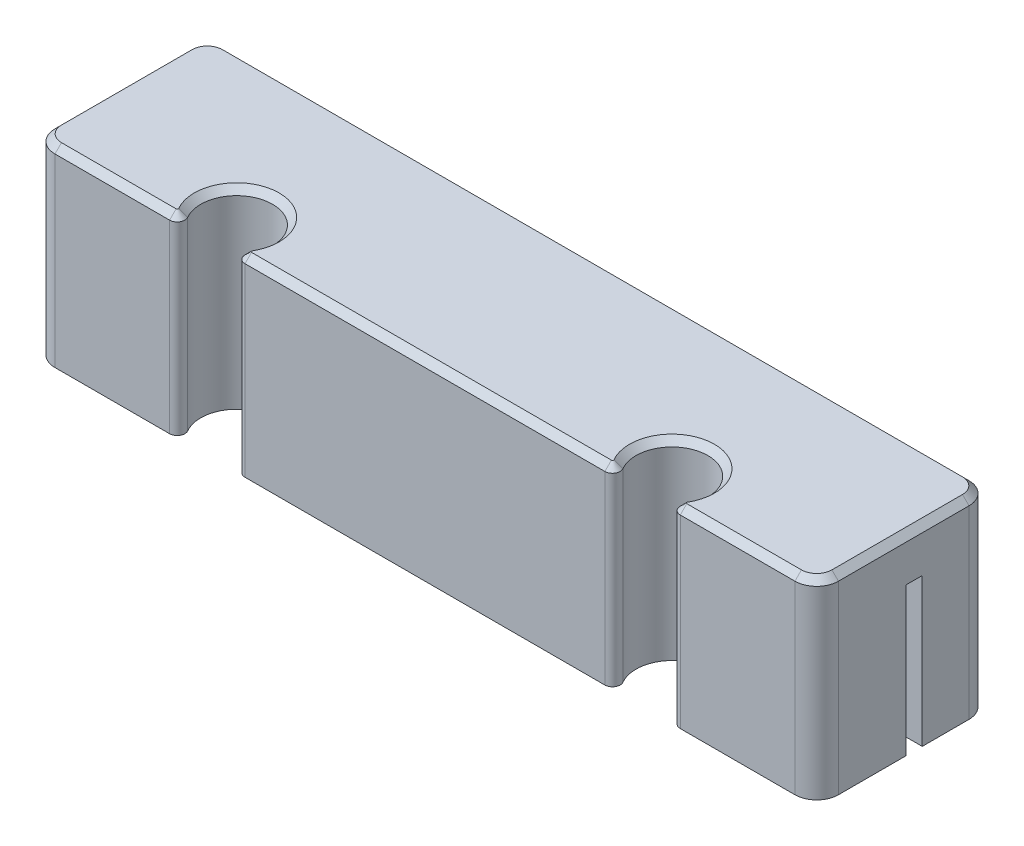
SolidWorks part; units mm, degrees
ref_plane "Front Plane" through (0, 0, 0) normal (0, 0, 1) x (1, 0, 0)
ref_plane "Top Plane" through (0, 0, 0) normal (0, 1, 0) x (1, 0, 0)
ref_plane "Right Plane" through (0, 0, 0) normal (1, 0, 0) x (0, 0, -1)
sketch "Sketch1" plane through (0, 0, 0) normal (0, 1, 0) x (1, 0, 0)
  line L0 (0, 19.8821) -> (0, -11.3954) construction
  line L1 (0, 0) -> (-18, 0)
  line L2 (0, -3.15) -> (-0.8, -3.15)
  line L3 (-0.8, -3.15) -> (-0.8, -2)
  line L4 (-0.8, -2) -> (-2, -2)
  line L5 (-2, -2) -> (-2, -3.15)
  line L6 (-2, -3.15) -> (-2.8, -3.15)
  line L7 (-2.8, -3.15) -> (-2.8, -2)
  line L8 (-2.8, -2) -> (-4, -2)
  line L9 (-4, -2) -> (-4, -3.15)
  line L10 (-4, -3.15) -> (-4.8, -3.15)
  line L11 (-4.8, -3.15) -> (-4.8, -2)
  line L12 (-4.8, -2) -> (-6, -2)
  line L13 (-6, -2) -> (-6, -3.15)
  line L14 (-6, -3.15) -> (-6.8, -3.15)
  line L15 (-6.8, -3.15) -> (-6.8, -2)
  line L16 (-6.8, -2) -> (-8, -2)
  line L17 (-8, -2) -> (-8, -3.15)
  line L18 (-8, -3.15) -> (-8.8, -3.15)
  line L19 (-8.8, -3.15) -> (-8.8, -2)
  line L20 (-8.8, -2) -> (-10, -2)
  line L21 (-10, -2) -> (-10, -3.15)
  line L22 (-10, -3.15) -> (-10.8, -3.15)
  line L23 (-10.8, -3.15) -> (-10.8, -2)
  line L24 (-10.8, -2) -> (-12, -2)
  line L25 (-12, -2) -> (-12, -3.15)
  line L26 (-12, -3.15) -> (-12.8, -3.15)
  line L27 (-12.8, -3.15) -> (-12.8, -2)
  line L28 (-12.8, -2) -> (-14, -2)
  line L29 (-14, -2) -> (-14, -3.15)
  line L30 (-14, -3.15) -> (-14.8, -3.15)
  line L31 (-14.8, -3.15) -> (-14.8, -2)
  line L32 (-14.8, -2) -> (-16, -2)
  line L33 (-16, -2) -> (-16, -3.15)
  line L34 (-16, -3.15) -> (-16.8, -3.15)
  line L35 (-16.8, -3.15) -> (-16.8, -2)
  line L36 (-16.8, -2) -> (-18, -2)
  line L38 (-18, -2) -> (-18, -3.15) [skipped]
  line L40 (0, -3.15) -> (0, -2)
  line L41 (0, -2) -> (1.2, -2)
  line L42 (1.2, -2) -> (1.2, -3.15)
  line L43 (1.2, -3.15) -> (2, -3.15)
  line L44 (2, -3.15) -> (2, -2)
  line L45 (2, -2) -> (3.2, -2)
  line L46 (3.2, -2) -> (3.2, -3.15)
  line L47 (3.2, -3.15) -> (4, -3.15)
  line L48 (4, -3.15) -> (4, -2)
  line L49 (4, -2) -> (5.2, -2)
  line L50 (5.2, -2) -> (5.2, -3.15)
  line L51 (5.2, -3.15) -> (6, -3.15)
  line L52 (6, -3.15) -> (6, -2)
  line L53 (6, -2) -> (7.2, -2)
  line L54 (7.2, -2) -> (7.2, -3.15)
  line L55 (7.2, -3.15) -> (8, -3.15)
  line L56 (8, -3.15) -> (8, -2)
  line L57 (8, -2) -> (9.2, -2)
  line L58 (9.2, -2) -> (9.2, -3.15)
  line L59 (9.2, -3.15) -> (10, -3.15)
  line L60 (10, -3.15) -> (10, -2)
  line L61 (10, -2) -> (11.2, -2)
  line L62 (11.2, -2) -> (11.2, -3.15)
  line L63 (11.2, -3.15) -> (12, -3.15)
  line L64 (12, -3.15) -> (12, -2)
  line L65 (12, -2) -> (13.2, -2)
  line L66 (13.2, -2) -> (13.2, -3.15)
  line L67 (13.2, -3.15) -> (14, -3.15)
  line L68 (14, -3.15) -> (14, -2)
  line L69 (14, -2) -> (15.2, -2)
  line L70 (15.2, -2) -> (15.2, -3.15)
  line L71 (15.2, -3.15) -> (16, -3.15)
  line L72 (16, -3.15) -> (16, -2)
  line L73 (16, -2) -> (17.2, -2)
  line L74 (17.2, -2) -> (17.2, -3.15)
  line L75 (17.2, -3.15) -> (18, -3.15)
  line L76 (18, -3.15) -> (18, -2)
  line L77 (0, 0) -> (18, 0)
  line L78 (18, 0) -> (18, -2)
  line L79 (-18, -2) -> (-18, 0)
  dimension "D1" = 36
  dimension "D2" = 0.8
  dimension "D3" = 1.15
  dimension "D4" = 2
  dimension "D6" = 2
  dimension "D7" = 2
  dimension "D5" = 9
  dimension "D8" = 9
extrude "Boss-Extrude1" add sketch "Sketch1" along normal blind 6.8
fillet "Fillet1" [suppressed] radius 0.5
fillet "Fillet2" [suppressed] radius 0.25
sketch "Sketch4" plane through (0, 6.8, 0) normal (0, 1, 0) x (1, 0, 0)
  line L0 (18, -3.15) -> (18, 0) construction
  line L1 (-18, 0) -> (18, 0)
  line L2 (-18, 0) -> (-18, -8)
  line L3 (-18, -8) -> (18, -8)
  line L4 (18, 0) -> (18, -8)
  dimension "D1" = 8
extrude "Boss-Extrude2" add sketch "Sketch4" along normal blind 2
sketch "Sketch5" plane through (0, 6.8, 0) normal (0, -1, 0) x (1, 0, 0)
  line L0 (18, 8) -> (18, 3.15) construction
  line L1 (-18, 8) -> (18, 8)
  line L2 (-18, 8) -> (-18, 3.9)
  line L3 (-18, 3.9) -> (18, 3.9)
  line L4 (18, 8) -> (18, 3.9)
  line L5 (18, 0) -> (-18, 0) construction
  dimension "D1" = 3.9
extrude "Boss-Extrude3" add sketch "Sketch5" along normal blind 6.8
sketch "Sketch6" plane through (0, 8.8, 0) normal (0, 1, 0) x (1, 0, 0)
  line L0 (-18, -3.9) -> (18, -3.9) construction
  line L1 (0, 6.6059) -> (0, -14.5665) construction
  circle A0 centre (-10, -6.65) radius 2.75 construction
  circle A1 centre (-10, -6.65) radius 1.65
  circle A2 centre (10, -6.65) radius 1.65
  point P5 (-10, -3.9)
  dimension "D1" = 5.5
  dimension "D3" = 3.3
  dimension "D2" = 20
extrude "Cut-Extrude1" cut sketch "Sketch6" against normal through all both and the other way through all
fillet "Fillet3" radius 0.35 4 edges at (10.9487, 4.4, 8) (9.0513, 4.4, 8) (-9.0513, 4.4, 8) (-10.9487, 4.4, 8)
fillet "Fillet4" radius 1 4 edges at (-18, 4.4, 8) (18, 4.4, 8) (18, 4.4, 0) (-18, 4.4, 0)
chamfer "Chamfer1" distance 0.3 angle 45 16 edges at (-8.5711, 8.8, 7.825) (-10, 8.8, 5) (0, 8.8, 8) (-11.4289, 8.8, 7.825) (8.5711, 8.8, 7.825) (-14.366, 8.8, 8) (10, 8.8, 5) (-17.7071, 8.8, 7.7071) (11.4289, 8.8, 7.825) (-18, 8.8, 4) (14.366, 8.8, 8) (-17.7071, 8.8, 0.2929) (17.7071, 8.8, 7.7071) (0, 8.8, 0) (17.7071, 8.8, 0.2929) (18, 8.8, 4)
